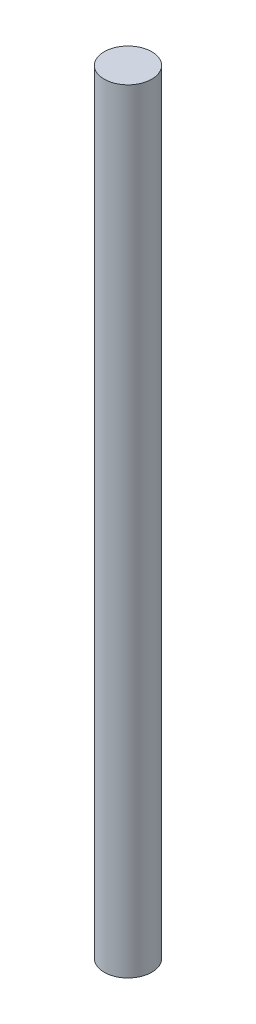
SolidWorks part; units mm, degrees
ref_plane "Alzado" through (0, 0, 0) normal (0, 0, 1) x (1, 0, 0)
ref_plane "Planta" through (0, 0, 0) normal (0, 1, 0) x (1, 0, 0)
ref_plane "Vista lateral" through (0, 0, 0) normal (1, 0, 0) x (0, 0, -1)
sketch "Croquis1" plane through (0, 0, 0) normal (0, 1, 0) x (1, 0, 0)
  circle A0 centre (0, 0) radius 4
  dimension "D1" = 8
extrude "Saliente-Extruir1" add sketch "Croquis1" along normal blind 130
